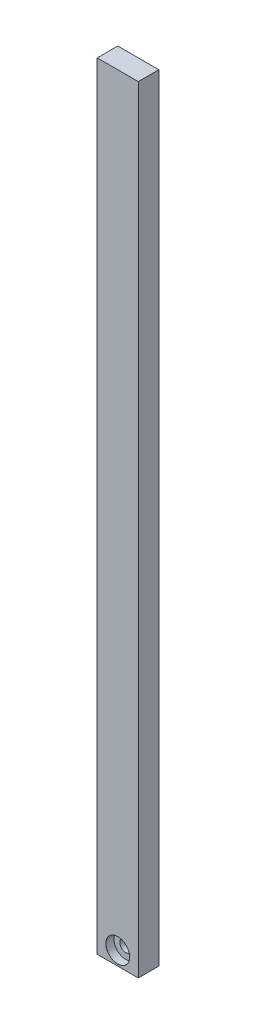
SolidWorks part; units mm, degrees
material "Liga 1060"
ref_plane "Plano frontal" through (0, 0, 0) normal (0, 0, 1) x (1, 0, 0)
ref_plane "Plano superior" through (0, 0, 0) normal (0, 1, 0) x (1, 0, 0)
ref_plane "Plano direito" through (0, 0, 0) normal (1, 0, 0) x (0, 0, -1)
sketch "Esboço1" plane through (0, 0, 0) normal (0, 0, 1) x (1, 0, 0)
  line L1 (9.525, -180) -> (-9.525, -180)
  line L2 (9.525, -180) -> (9.525, 180)
  line L3 (9.525, 180) -> (-9.525, 180)
  line L4 (-9.525, -180) -> (-9.525, 180)
  line L5 (9.525, -180) -> (-9.525, 180) construction
  line L6 (9.525, 180) -> (-9.525, -180) construction
  point P0 (0, 0)
  dimension "D1" = 19.05
  dimension "D2" = 360
extrude "Ressalto-extrusão1" add sketch "Esboço1" along normal blind 9.525
sketch "Esboço3" plane through (0, 0, 9.525) normal (0, 0, 1) x (1, 0, 0)
  line L0 (0, -180) -> (0, -173.65) construction
  line L1 (-9.525, -180) -> (9.525, -180) construction
  circle A0 centre (0, -173.65) radius 2.5
  dimension "D1" = 5
  dimension "D2" = 6.35
extrude "Corte-extrusão1" cut sketch "Esboço3" against normal through all
hole_wizard "Rebaixo para parafuso com cabeça panela de M51" positions "Esboço4" profile "Esboço5" counterbore size "M5" standard "ISO" end condition through all
sketch "Esboço4" plane through (0, 0, 9.525) normal (0, 0, 1) x (1, 0, 0)
  point P0 (0, -173.65)
sketch "Esboço5" plane through (0, -173.65, 9.525) normal (1, 0, 0) x (0, -1, 0)
  line L0 (0, 0) -> (0, 9.525)
  line L1 (0, 9.525) -> (2.75, 9.525)
  line L3 (2.75, 9.525) -> (2.75, 3.7)
  line L4 (5.5, 3.7) -> (2.75, 3.7)
  line L5 (5.5, 3.7) -> (5.5, 0.025)
  line L6 (5.5, 0.025) -> (5.525, 0)
  line L7 (5.525, 0) -> (0, 0)
  line L8 (-5.5, 0.025) -> (-5.525, 0) construction
  line L11 (0, -6.35) -> (0, 107.95) construction
  dimension "Thru Hole Dia." = 5.5
  dimension "Thru Hole Depth" = 9.525
  dimension "C'Bore Dia." = 11
  dimension "C'Bore Depth" = 3.7
  dimension "Near C'Sink Dia." = 11.05
  dimension "Near C'Sink Angle" = 90
